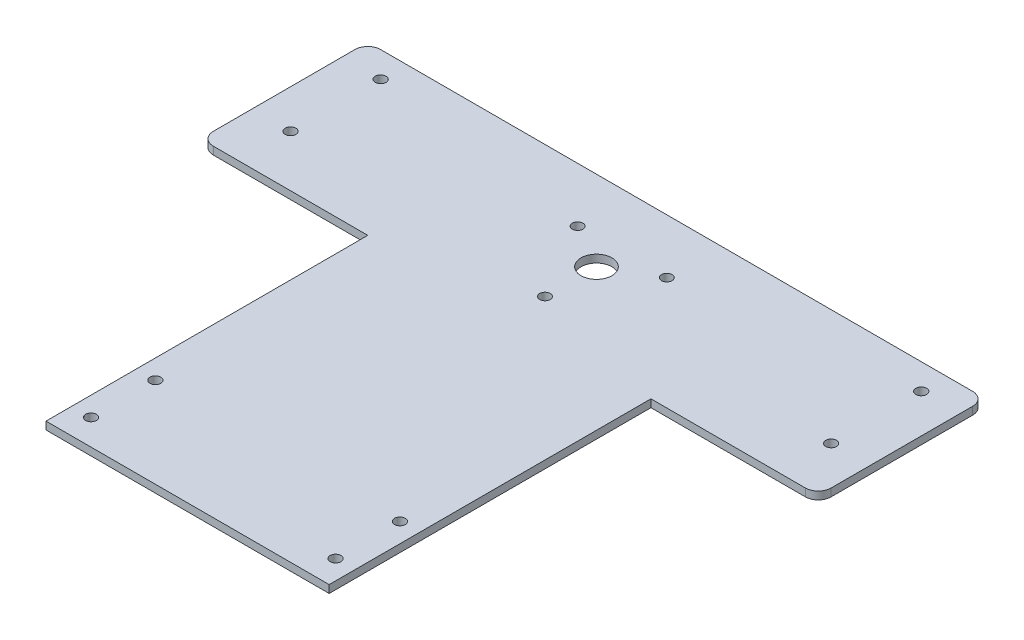
SolidWorks part; units mm, degrees
material "Thornel Mat VMA"
ref_plane "前视基准面" through (0, 0, 0) normal (0, 0, 1) x (1, 0, 0)
ref_plane "上视基准面" through (0, 0, 0) normal (0, 1, 0) x (1, 0, 0)
ref_plane "右视基准面" through (0, 0, 0) normal (1, 0, 0) x (0, 0, -1)
sketch "草图1" plane through (0, 0, 0) normal (0, 1, 0) x (1, 0, 0)
  line L0 (-105, 55.625) -> (-105, -9.375) construction
  line L1 (-120, -9.375) -> (120, -9.375)
  line L2 (-120, -9.375) -> (-120, 55.625)
  line L3 (-120, 55.625) -> (120, 55.625)
  line L4 (120, -9.375) -> (120, 55.625)
  line L5 (-120, -9.375) -> (120, 55.625) construction
  line L6 (-120, 55.625) -> (120, -9.375) construction
  line L7 (0, 55.625) -> (0, -9.375) construction
  line L8 (0, -71.875) -> (0, -9.375) construction
  line L9 (-66.9961, -9.375) -> (13.0039, -9.375)
  line L11 (-55, -134.375) -> (55, -134.375)
  line L12 (-55, -134.375) -> (-55, -9.375)
  line L13 (-55, -9.375) -> (55, -9.375)
  line L14 (55, -134.375) -> (55, -9.375)
  line L15 (-55, -134.375) -> (55, -9.375) construction
  line L16 (-55, -9.375) -> (55, -134.375) construction
  circle A0 centre (-105, 45.625) radius 2.1
  circle A1 centre (-105, 10.625) radius 2.1
  circle A2 centre (105, 10.625) radius 2.1
  circle A3 centre (105, 45.625) radius 2.1
  point P0 (0, 23.125)
  dimension "D1" = 65
  dimension "D2" = 240
  dimension "D3" = 15
  dimension "D4" = 35
  dimension "D5" = 20
  dimension "D6" = 125
  dimension "D7" = 55
extrude "凸台-拉伸1" add sketch "草图1" along normal blind 3 contours L1 L4 L3 L2 A2 A1 A0 A3 | L11 L14 L1 L9 L12
sketch "草图5" plane through (0, 3, 0) normal (0, 1, 0) x (1, 0, 0)
  line L0 (0, 0) -> (0, -71.875) construction
  line L2 (-55, -134.375) -> (55, -134.375)
  line L3 (-55, -134.375) -> (-55, -9.375)
  line L5 (55, -134.375) -> (55, -9.375)
  line L6 (-55, -134.375) -> (55, -9.375) construction
  line L7 (-55, -9.375) -> (55, -134.375) construction
  line L8 (-47.5, -124.375) -> (47.5, -124.375) construction
  line L9 (47.5, -124.375) -> (47.5, -99.375) construction
  line L10 (-55, -9.375) -> (55, -9.375)
  line L11 (-120, -9.375) -> (-55, -9.375) construction
  circle A0 centre (-47.5, -124.375) radius 2.1
  circle A2 centre (47.5, -124.375) radius 2.1
  circle A3 centre (47.5, -99.375) radius 2.1
  circle A4 centre (-47.5, -99.375) radius 2.1
  point P12 (0, -124.375)
  dimension "D6" = 4.2
  dimension "D7" = 4.2
  dimension "D1" = 125
  dimension "D2" = 110
  dimension "D3" = 95
  dimension "D4" = 25
  dimension "D5" = 10
  dimension "D8" = 0
sketch "草图3" plane through (0, 3, 0) normal (0, 1, 0) x (1, 0, 0)
  line L0 (-1000, 24.4697) -> (49000, 24.4697) construction
  line L2 (0, 59.375) -> (0, -28.125) construction
  circle A6 centre (0, 24.4697) radius 6
  circle A10 centre (0, 4.4697) radius 2.05
  circle A11 centre (-17.3205, 34.4697) radius 2.05
  circle A12 centre (17.3205, 34.4697) radius 2.05
  point P15 (0, 24.4697)
  point P16 (0, 19.4852)
  dimension "D1" = 20
fillet "圆角1" radius 5 4 edges at (-120, 1.5, 9.375) (-120, 1.5, -55.625) (120, 1.5, -55.625) (120, 1.5, 9.375)
extrude "切除-拉伸4" cut sketch "草图5" against normal blind 10 contours A3 | A2 | A4 | A0
fillet "圆角2" [suppressed] radius 10
extrude "切除-拉伸5" cut sketch "草图3" against normal blind 10
